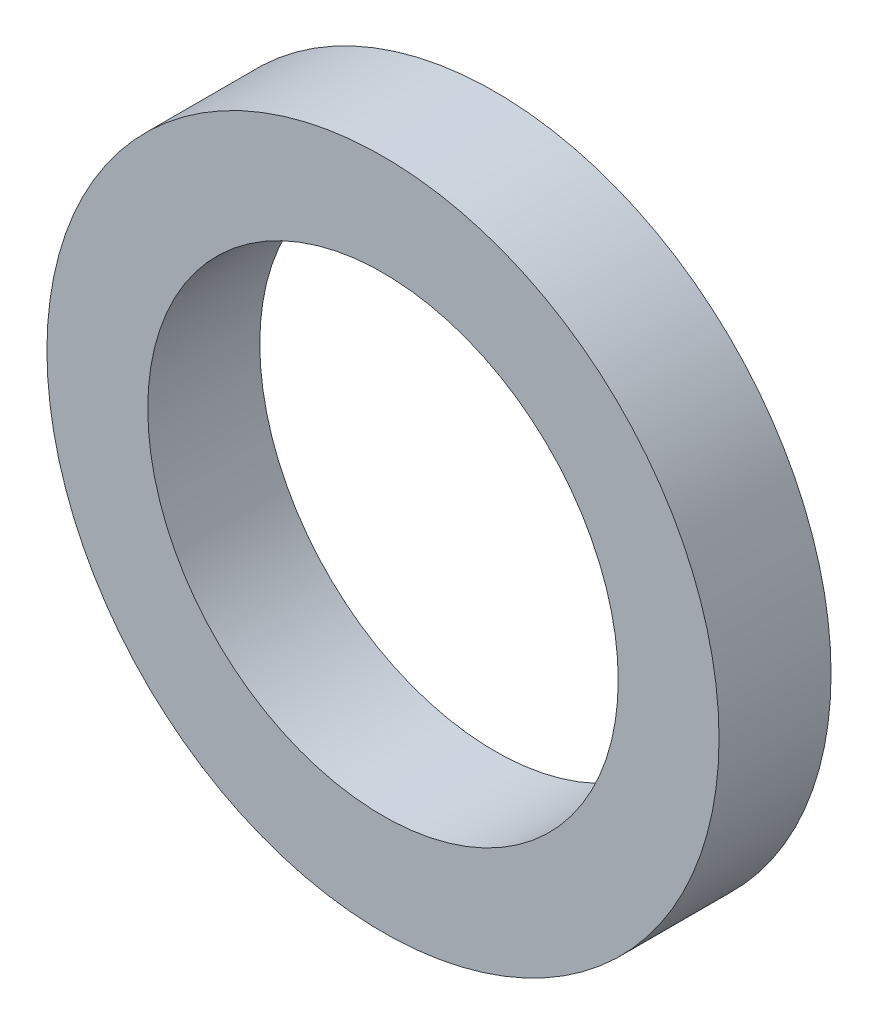
SolidWorks part; units mm, degrees
ref_plane "Front Plane" through (0, 0, 0) normal (0, 0, 1) x (1, 0, 0)
ref_plane "Top Plane" through (0, 0, 0) normal (0, 1, 0) x (1, 0, 0)
ref_plane "Right Plane" through (0, 0, 0) normal (1, 0, 0) x (0, 0, -1)
sketch "Sketch1" plane through (0, 0, 0) normal (0, 0, 1) x (1, 0, 0)
  circle A0 centre (0, 0) radius 1.5
  circle A1 centre (0, 0) radius 1.05
extrude "Spacer" add sketch "Sketch1" along normal blind 0.5
